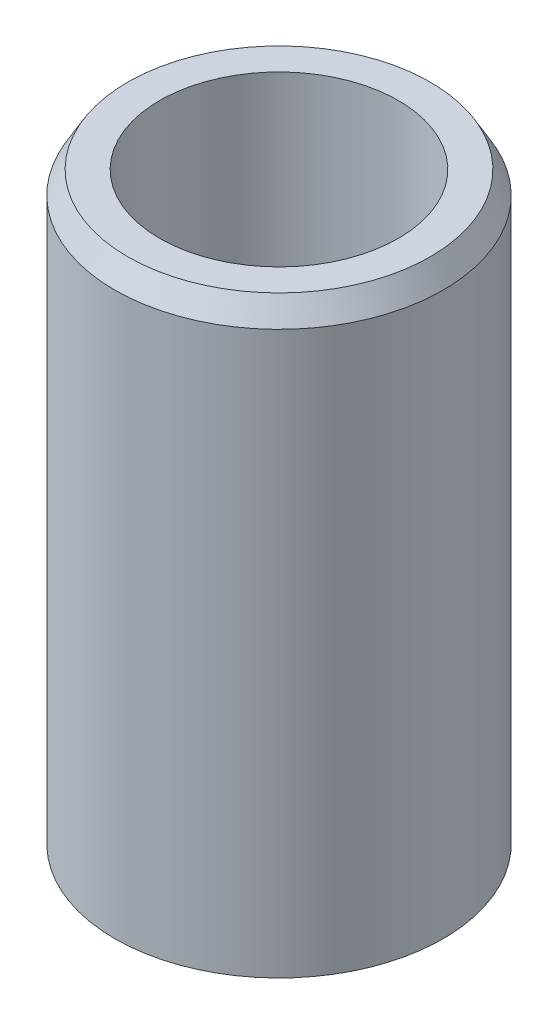
SolidWorks part; units mm, degrees
material "AISI Type A2 Tool Steel"
ref_plane "Front Plane" through (0, 0, 0) normal (0, 0, 1) x (1, 0, 0)
ref_plane "Top Plane" through (0, 0, 0) normal (0, 1, 0) x (1, 0, 0)
ref_plane "Right Plane" through (0, 0, 0) normal (1, 0, 0) x (0, 0, -1)
sketch "Sketch1" plane through (0, 0, 0) normal (0, 1, 0) x (1, 0, 0)
  circle A0 centre (0, 0) radius 22
  circle A1 centre (0, 0) radius 16
  dimension "D1" = 32
  dimension "D2" = 44
extrude "Boss-Extrude1" add sketch "Sketch1" along normal blind 80
chamfer "Chamfer1" distance 3 angle 30 2 edges at (0, 0, 22) (0, 80, 22)
